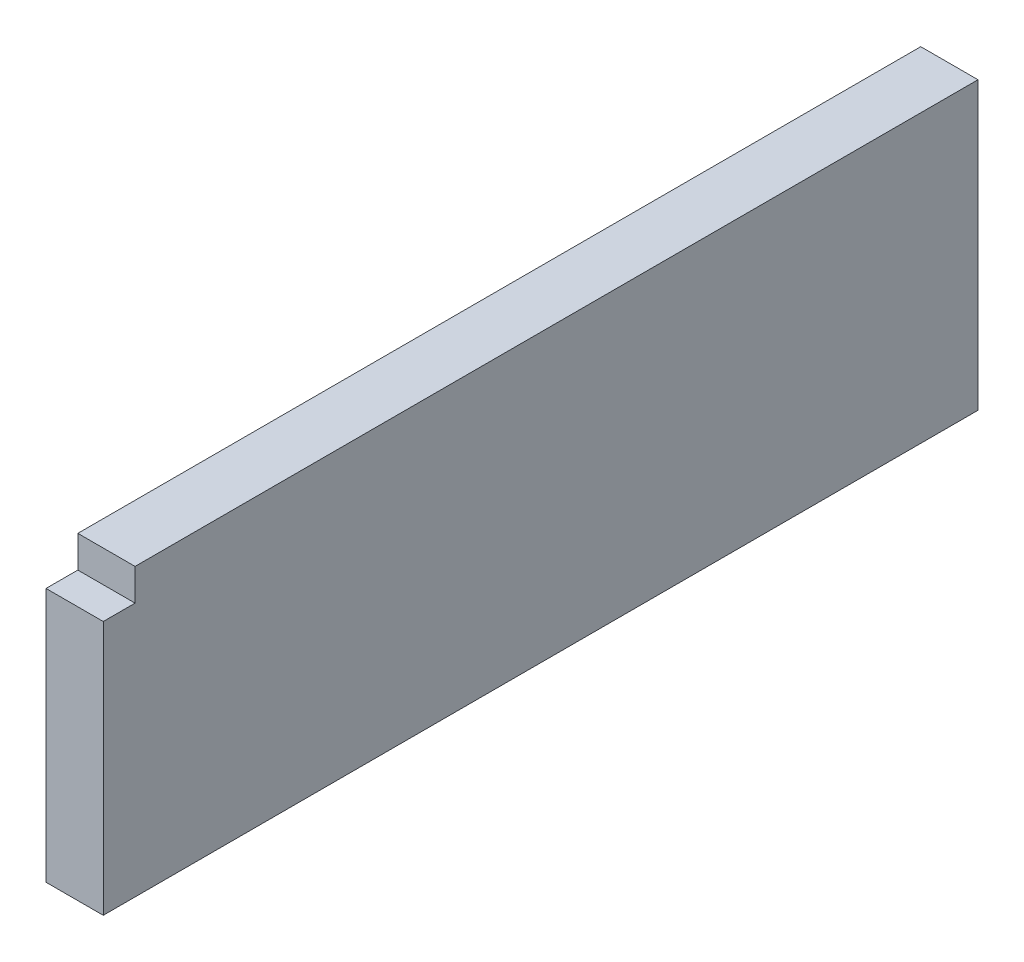
SolidWorks part; units mm, degrees
material "Mahogany"
ref_plane "Front Plane" through (0, 0, 0) normal (0, 0, 1) x (1, 0, 0)
ref_plane "Top Plane" through (0, 0, 0) normal (0, 1, 0) x (1, 0, 0)
ref_plane "Right Plane" through (0, 0, 0) normal (1, 0, 0) x (0, 0, -1)
sketch "Sketch1" plane through (0, 0, 0) normal (1, 0, 0) x (0, 0, -1)
  line L0 (-137.5, 35) -> (-137.5, -45)
  line L1 (-137.5, -45) -> (137.5, -45)
  line L2 (-137.5, -45) -> (-137.5, 45) construction
  line L3 (-137.5, 45) -> (137.5, 45) construction
  line L4 (137.5, -45) -> (137.5, 45)
  line L5 (-137.5, -45) -> (137.5, 45) construction
  line L6 (-137.5, 45) -> (137.5, -45) construction
  line L7 (-137.5, 45) -> (-127.5, 45) construction
  line L8 (-137.5, 45) -> (-137.5, 35) construction
  line L9 (-137.5, 35) -> (-127.5, 35)
  line L10 (-127.5, 45) -> (-127.5, 35)
  line L11 (-127.5, 45) -> (137.5, 45)
  point P0 (0, 0)
  dimension "D1" = 275
  dimension "D2" = 90
  dimension "D3" = 10
extrude "Boss-Extrude1" add sketch "Sketch1" along normal mid plane 18
